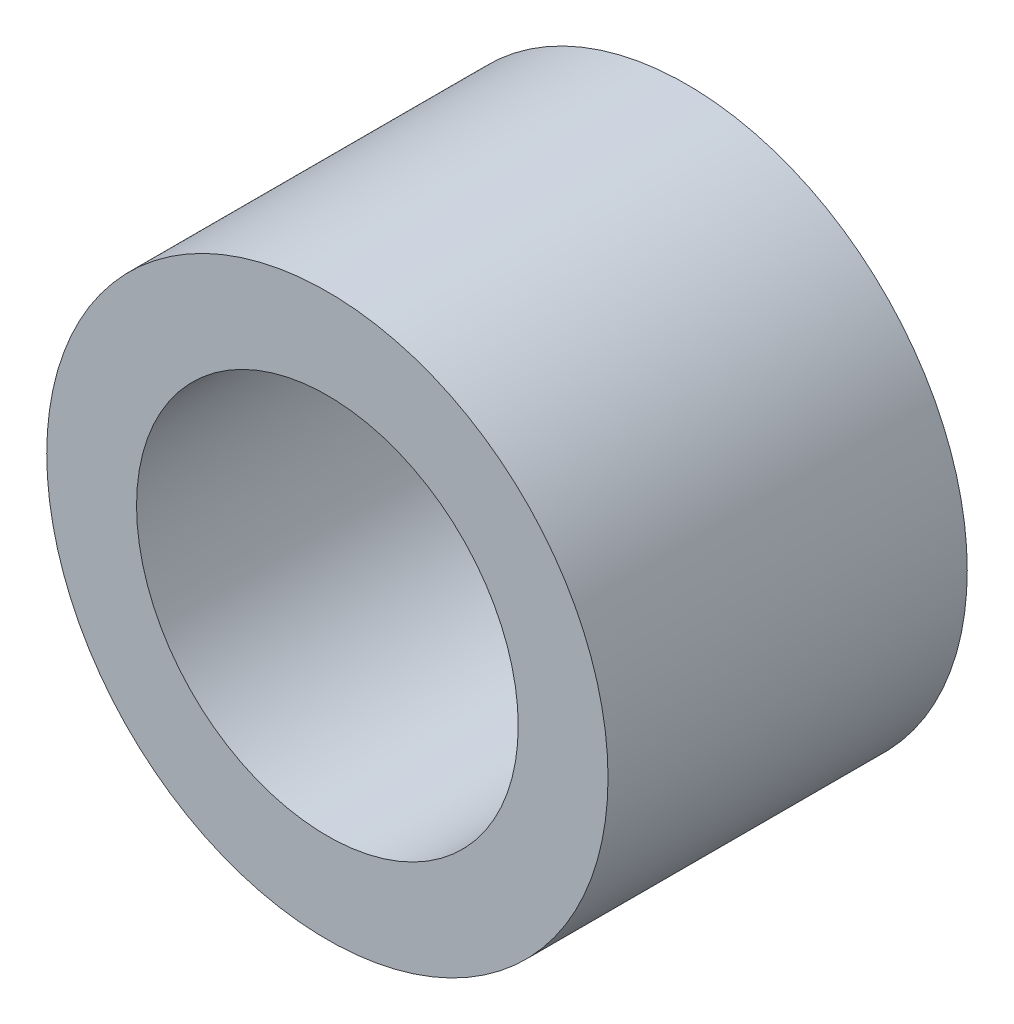
SolidWorks part; units mm, degrees
ref_plane "Спереди" through (0, 0, 0) normal (0, 0, 1) x (1, 0, 0)
ref_plane "Сверху" through (0, 0, 0) normal (0, 1, 0) x (1, 0, 0)
ref_plane "Справа" through (0, 0, 0) normal (1, 0, 0) x (0, 0, -1)
sketch "Эскиз1" plane through (0, 0, 0) normal (0, 0, 1) x (1, 0, 0)
  circle A0 centre (0, 0) radius 12.5
  circle A1 centre (0, 0) radius 8.5
extrude "Needle_bearing" add sketch "Эскиз1" along normal blind 16 from offset 55.5
